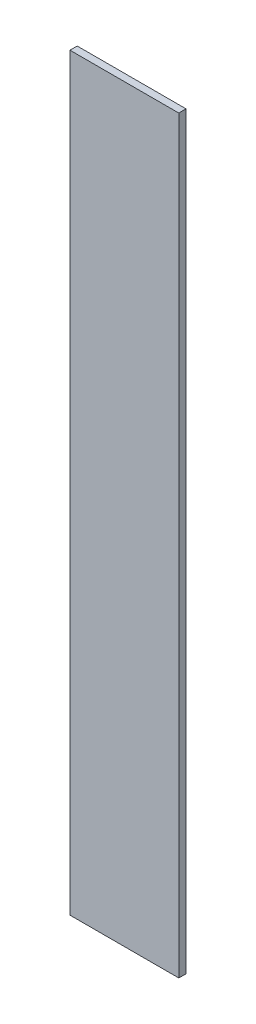
SolidWorks part; units mm, degrees
ref_plane "Front Plane" through (0, 0, 0) normal (0, 0, 1) x (1, 0, 0)
ref_plane "Top Plane" through (0, 0, 0) normal (0, 1, 0) x (1, 0, 0)
ref_plane "Right Plane" through (0, 0, 0) normal (1, 0, 0) x (0, 0, -1)
sketch "Sketch1" plane through (0, 0, 0) normal (0, 0, 1) x (1, 0, 0)
  line L1 (0, 0) -> (3, 0)
  line L2 (0, 0) -> (0, 20.65)
  line L3 (0, 20.65) -> (3, 20.65)
  line L4 (3, 0) -> (3, 20.65)
  dimension "D1" = 3
  dimension "D2" = 20.65
extrude "Boss-Extrude1" add sketch "Sketch1" along normal blind 0.2
